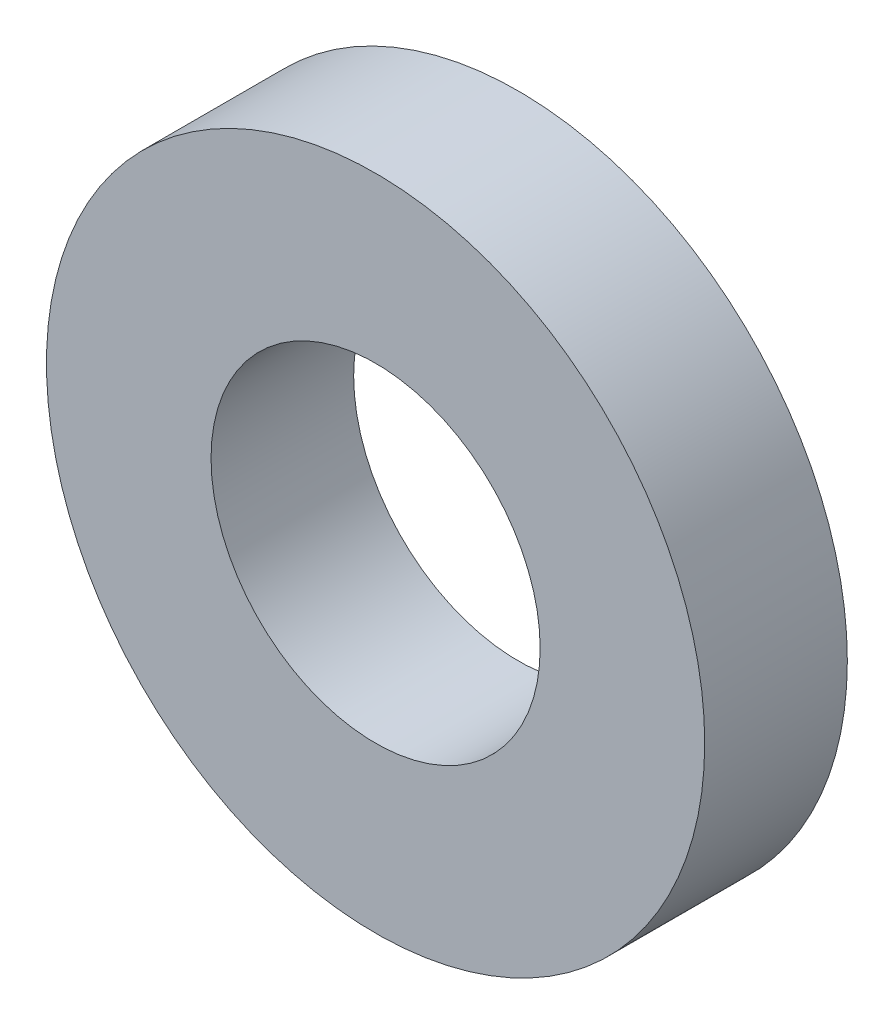
SolidWorks part; units mm, degrees
ref_plane "Front Plane" through (0, 0, 0) normal (0, 0, 1) x (1, 0, 0)
ref_plane "Top Plane" through (0, 0, 0) normal (0, 1, 0) x (1, 0, 0)
ref_plane "Right Plane" through (0, 0, 0) normal (1, 0, 0) x (0, 0, -1)
sketch "Sketch1" plane through (0, 0, 0) normal (0, 0, 1) x (1, 0, 0)
  circle A0 centre (0, 0) radius 1.5
  circle A1 centre (0, 0) radius 3
  dimension "D1" = 6
  dimension "D2" = 3
extrude "Boss-Extrude1" add sketch "Sketch1" along normal mid plane 1.3
